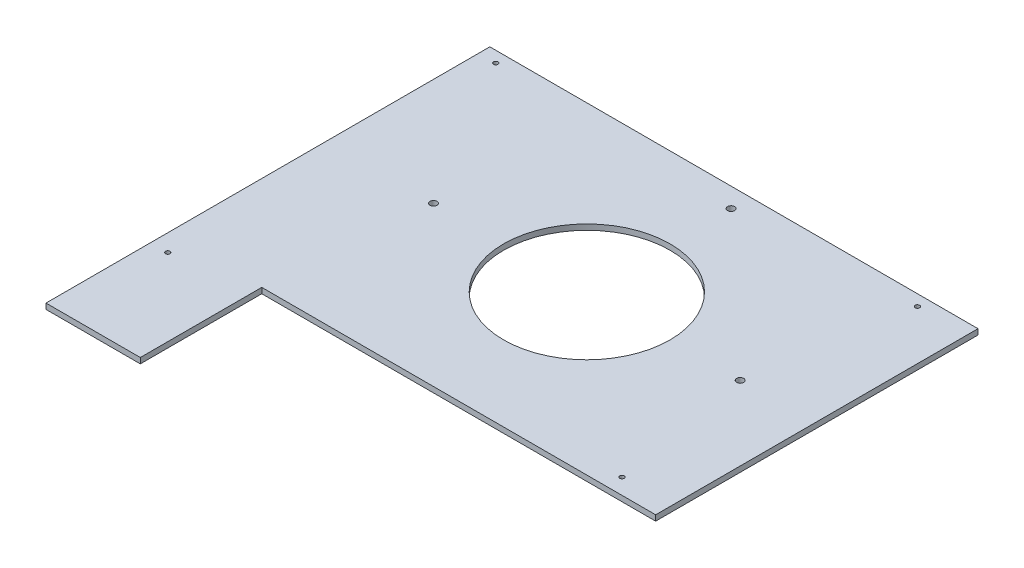
SolidWorks part; units mm, degrees
ref_plane "Alzado" through (0, 0, 0) normal (0, 0, 1) x (1, 0, 0)
ref_plane "Planta" through (0, 0, 0) normal (0, 1, 0) x (1, 0, 0)
ref_plane "Vista lateral" through (0, 0, 0) normal (1, 0, 0) x (0, 0, -1)
sketch "Croquis2" plane through (0, 0, 0) normal (0, 1, 0) x (1, 0, 0)
  line L0 (-164.0241, 177.5689) -> (-164.0241, -142.4311)
  line L4 (275.9759, 177.5689) -> (275.9759, -112.9585)
  line L31 (-79.0241, -112.9585) -> (275.9759, -112.9585)
  line L35 (-79.0241, -112.9585) -> (-79.0241, -142.4311)
  line L40 (275.9759, 177.5689) -> (-164.0241, 177.5689)
  line L43 (-79.0241, -112.9585) -> (-79.0241, 177.5689) construction
  line L45 (-84.0241, -222.4267) -> (-84.0241, 177.5689) construction
  line L46 (220.9759, 177.5689) -> (220.9759, -112.9585) construction
  line L48 (225.9759, 177.5689) -> (225.9759, -112.9585) construction
  line L49 (-164.0241, -142.4311) -> (-164.0241, -189.2567)
  line L51 (-79.0241, -189.2567) -> (-79.0241, -142.4311)
  line L52 (-164.0241, -189.2567) -> (-164.0241, -222.4267)
  line L53 (-164.0241, -222.4267) -> (-79.0241, -222.4267)
  line L54 (-79.0241, -222.4267) -> (-79.0241, -189.2567)
  circle A3 centre (70.9759, 30.0258) radius 75
  circle A9 centre (-148.6131, 167.5689) radius 2
  circle A10 centre (-148.6131, -128.1451) radius 2
  circle A20 centre (231.3869, -98.6725) radius 2
  circle A21 centre (231.3869, 167.5689) radius 2
  circle A28 centre (209.1759, 30.0258) radius 3.175
  circle A29 centre (-67.2241, 30.0258) radius 3.175
  circle A40 centre (70.9759, 160.0258) radius 3.175
  point P0 (70.9759, 30.0258)
  point P13 (70.9759, 30.0258)
  point P26 (73.475, 30.0258)
  point P29 (70.9759, 7.6644)
  point P51 (13.8491, 7.5952)
  point P54 (13.6242, 7.6644)
  point P68 (41.8242, 35.8644)
  dimension "D2" = 150
  dimension "D3" = 50
  dimension "D10" = 130
  dimension "D11" = 6.35
  dimension "D13" = 6.35
  dimension "D16" = 10
  dimension "D17" = 10
  dimension "D8" = 138.2
  dimension "D9" = 6.35
  dimension "D4" = 80
  dimension "D5" = 5
  dimension "D6" = 150
  dimension "D7" = 150
  dimension "D12" = 138.2
  dimension "D14" = 5
  dimension "D15" = 320
  dimension "D18" = 33.17
extrude "Saliente-Extruir2" add sketch "Croquis2" along normal blind 5
sketch "Croquis3" plane through (0, 5, 0) normal (0, 1, 0) x (1, 0, 0)
  point P0 (70.9759, 30.0258)
